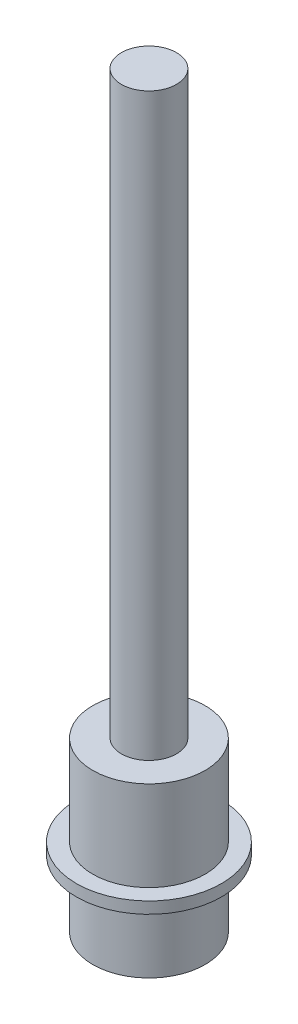
SolidWorks part; units mm, degrees
ref_plane "Front Plane" through (0, 0, 0) normal (0, 0, 1) x (1, 0, 0)
ref_plane "Top Plane" through (0, 0, 0) normal (0, 1, 0) x (1, 0, 0)
ref_plane "Right Plane" through (0, 0, 0) normal (1, 0, 0) x (0, 0, -1)
sketch "Sketch1" plane through (0, 0, 0) normal (0, 1, 0) x (1, 0, 0)
  circle A0 centre (0, 0) radius 4.845
  circle A1 centre (0, 0) radius 2.375
  dimension "D1" = 9.69
  dimension "D2" = 4.75
extrude "Boss-Extrude1" add sketch "Sketch1" along normal blind 5.75
sketch "Sketch4" plane through (0, 5.75, 0) normal (0, 1, 0) x (1, 0, 0)
  circle A0 centre (0, 0) radius 6.25
  circle A1 centre (0, 0) radius 2.375
  dimension "D1" = 12.5
extrude "Boss-Extrude4" add sketch "Sketch4" along normal blind 1
sketch "Sketch5" plane through (0, 6.75, 0) normal (0, 1, 0) x (1, 0, 0)
  circle A0 centre (0, 0) radius 2.375
  circle A1 centre (0, 0) radius 4.845
  dimension "D1" = 9.69
extrude "Boss-Extrude5" add sketch "Sketch5" along normal blind 5.75
sketch "Sketch6" plane through (0, 12.5, 0) normal (0, 1, 0) x (1, 0, 0)
  circle A0 centre (0, 0) radius 4.845
extrude "Boss-Extrude6" add sketch "Sketch6" along normal blind 2
sketch "Sketch7" plane through (0, 14.5, 0) normal (0, 1, 0) x (1, 0, 0)
  circle A0 centre (0, 0) radius 2.375
  dimension "D1" = 4.75
extrude "Boss-Extrude7" add sketch "Sketch7" along normal blind 50
